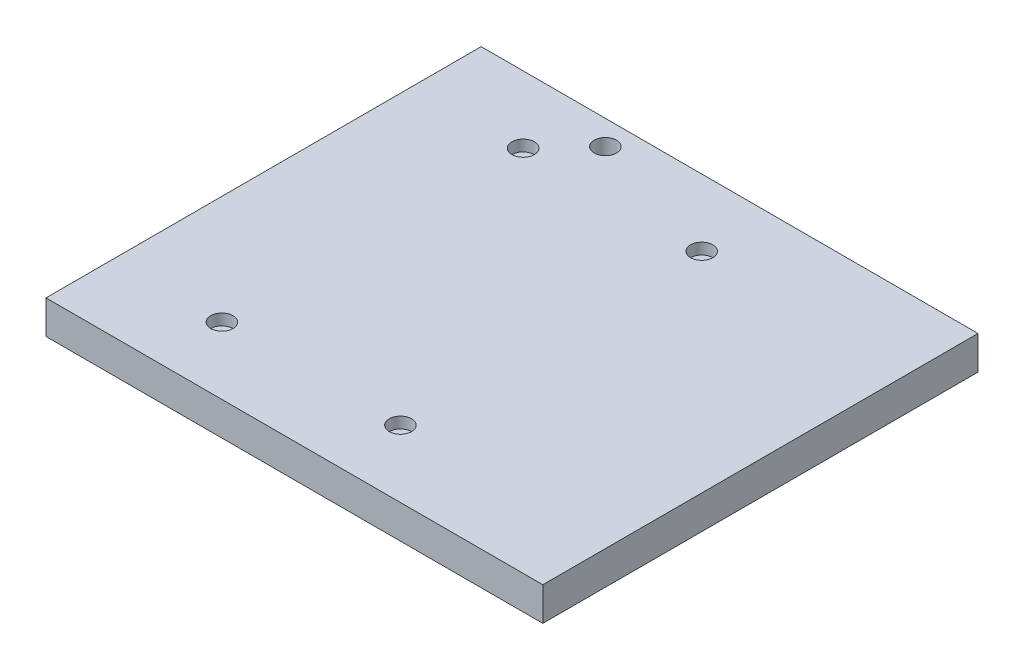
SolidWorks part; units mm, degrees
ref_plane "Front Plane" through (0, 0, 0) normal (0, 0, 1) x (1, 0, 0)
ref_plane "Top Plane" through (0, 0, 0) normal (0, 1, 0) x (1, 0, 0)
ref_plane "Right Plane" through (0, 0, 0) normal (1, 0, 0) x (0, 0, -1)
sketch "Sketch1" plane through (0, 0, 0) normal (0, 1, 0) x (1, 0, 0)
  line L1 (0, 0) -> (355.26, 0)
  line L2 (0, 0) -> (0, -390)
  line L3 (0, -390) -> (355.26, -390)
  line L4 (355.26, 0) -> (355.26, -390)
  dimension "D1" = 355.26
  dimension "D2" = 390
extrude "Boss-Extrude1" add sketch "Sketch1" along normal blind 30
ref_plane "Plane1" through (0, 0, 195) normal (0, 0, 1) x (1, 0, 0)
ref_plane "Plane2" through (177.63, 0, 0) normal (-1, 0, 0) x (0, 0, 1)
sketch "Sketch3" plane through (355.26, 0, 0) normal (1, 0, 0) x (0, 0, -1)
  line L1 (-390, 30) -> (0, 30)
  line L2 (-390, 30) -> (-390, 0)
  line L3 (-390, 0) -> (0, 0)
  line L4 (0, 30) -> (0, 0)
extrude "Boss-Extrude2" add sketch "Sketch3" along normal blind 90
sketch "Sketch4" plane through (0, 30, 0) normal (0, 1, 0) x (1, 0, 0)
  line L0 (445.26, 0) -> (0, 0) construction
  line L1 (0, 0) -> (0, -390) construction
  circle A0 centre (97.63, -60) radius 10
  dimension "D1" = 20
  dimension "D2" = 60
  dimension "D3" = 97.63
extrude "Cut-Extrude1" cut sketch "Sketch4" against normal blind 10
mirror "Mirror1" about plane through (177.63, 0, 0) normal (-1, 0, 0) of "Cut-Extrude1"
mirror "Mirror2" about plane through (0, 0, 195) normal (0, 0, 1) of "Mirror1", "Cut-Extrude1"
sketch "Sketch7" plane through (0, 0, 0) normal (0, -1, 0) x (1, 0, 0)
  line L0 (16.5, 195) -> (-16.5, 195) construction
  line L1 (355.26, 380) -> (20, 380)
  line L2 (355.26, 380) -> (355.26, 10)
  line L3 (355.26, 10) -> (20, 10)
  line L4 (20, 380) -> (20, 10)
  line L5 (355.26, 380) -> (20, 10) construction
  line L6 (355.26, 10) -> (20, 380) construction
  line L7 (0, 0) -> (0, 390) construction
  point P0 (187.63, 195)
  dimension "D1" = 335.26
  dimension "D2" = 370
  dimension "D3" = 20
extrude "Cut-Extrude3" cut sketch "Sketch7" against normal blind 10
sketch "Sketch8" plane through (0, 30, 0) normal (0, 1, 0) x (1, 0, 0)
  circle A0 centre (133.2448, -21.9404) radius 10
  dimension "D1" = 20
extrude "Cut-Extrude4" cut sketch "Sketch8" against normal blind 87
